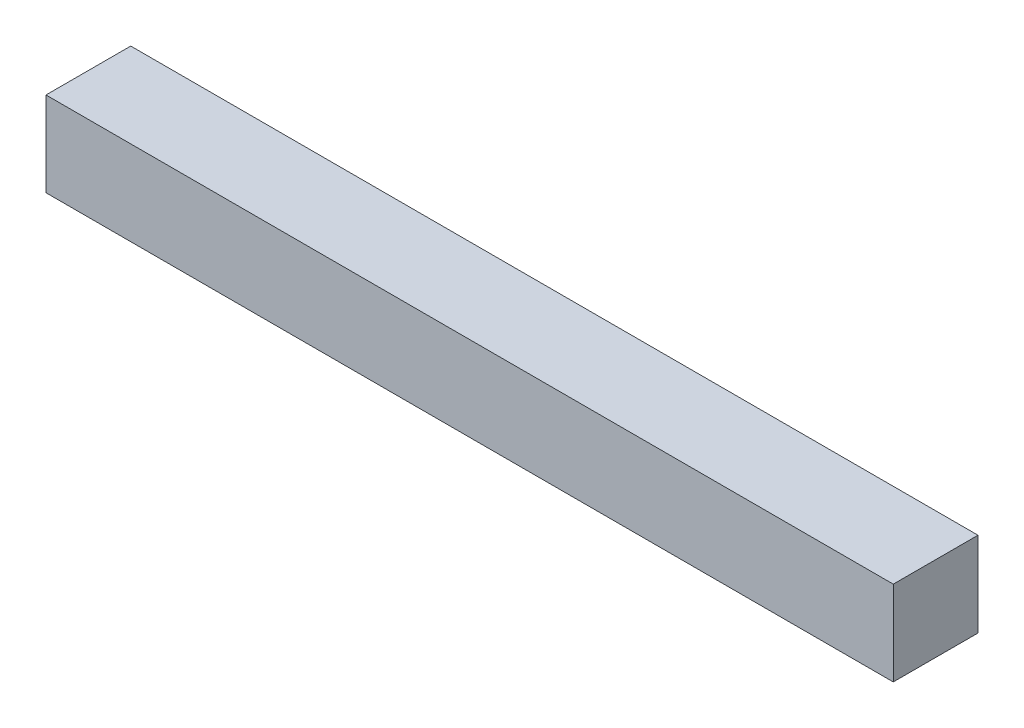
SolidWorks part; units mm, degrees
ref_plane "Front" through (0, 0, 0) normal (0, 0, 1) x (1, 0, 0)
ref_plane "Top" through (0, 0, 0) normal (0, 1, 0) x (1, 0, 0)
ref_plane "Right" through (0, 0, 0) normal (1, 0, 0) x (0, 0, -1)
sketch "Sketch1" plane through (0, 0, 0) normal (1, 0, 0) x (0, 0, -1)
  line L1 (-40, 25.8065) -> (-10, 25.8065)
  line L2 (-40, 25.8065) -> (-40, -4.1935)
  line L3 (-40, -4.1935) -> (-10, -4.1935)
  line L4 (-10, 25.8065) -> (-10, -4.1935)
  dimension "D1" = 30
  dimension "D2" = 30
extrude "Boss-Extrude1" add sketch "Sketch1" along normal blind 300
